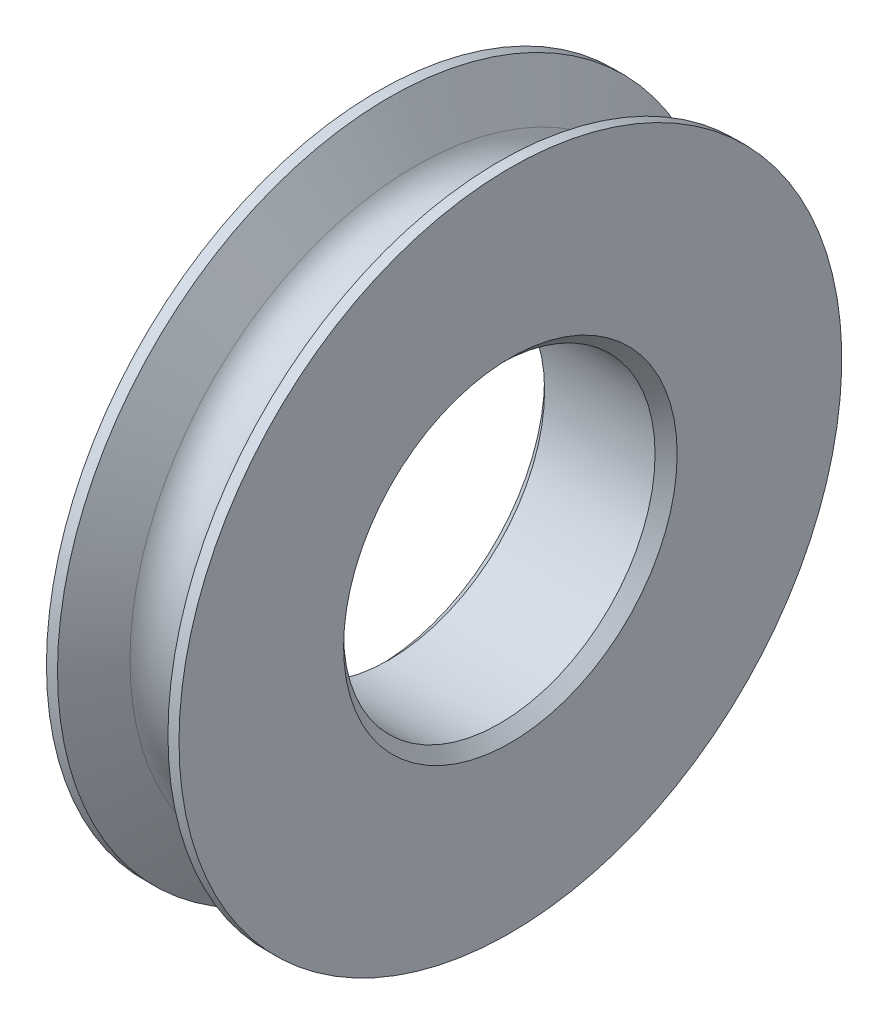
SolidWorks part; units mm, degrees
material "尼龙 101"
ref_plane "Front" through (0, 0, 0) normal (0, 0, 1) x (1, 0, 0)
ref_plane "Top" through (0, 0, 0) normal (0, 1, 0) x (1, 0, 0)
ref_plane "Right" through (0, 0, 0) normal (1, 0, 0) x (0, 0, -1)
sketch "草图1" plane through (0, 0, 0) normal (0, 0, 1) x (1, 0, 0)
  line L0 (-10.2331, 0) -> (17.0496, 0) construction
  line L1 (0, 0) -> (0, 16.8354) construction
  line L2 (-3, 7.05) -> (3, 7.05)
  line L3 (3, 7.05) -> (3, 15)
  line L4 (3, 15) -> (2.5, 15)
  line L5 (2.5, 15) -> (1.299, 12.9199)
  line L6 (-2.5, 15) -> (-1.299, 12.9199)
  line L7 (-3, 15) -> (-2.5, 15)
  line L8 (-3, 7.05) -> (-3, 15)
  arc A0 (-1.299, 12.9199) -> (1.299, 12.9199) centre (0, 13.6699) ccw
  point P16 (0, 7.05)
  dimension "D1" = 3
  dimension "D2" = 7.05
  dimension "D3" = 3
  dimension "D4" = 30
  dimension "D5" = 0.5
  dimension "D6" = 15
revolve "旋转1" add sketch "草图1" angle 360 about L0
chamfer "倒角1" distance 0.5 angle 45 2 edges at (3, 0, 7.05) (-3, 0, 7.05)
